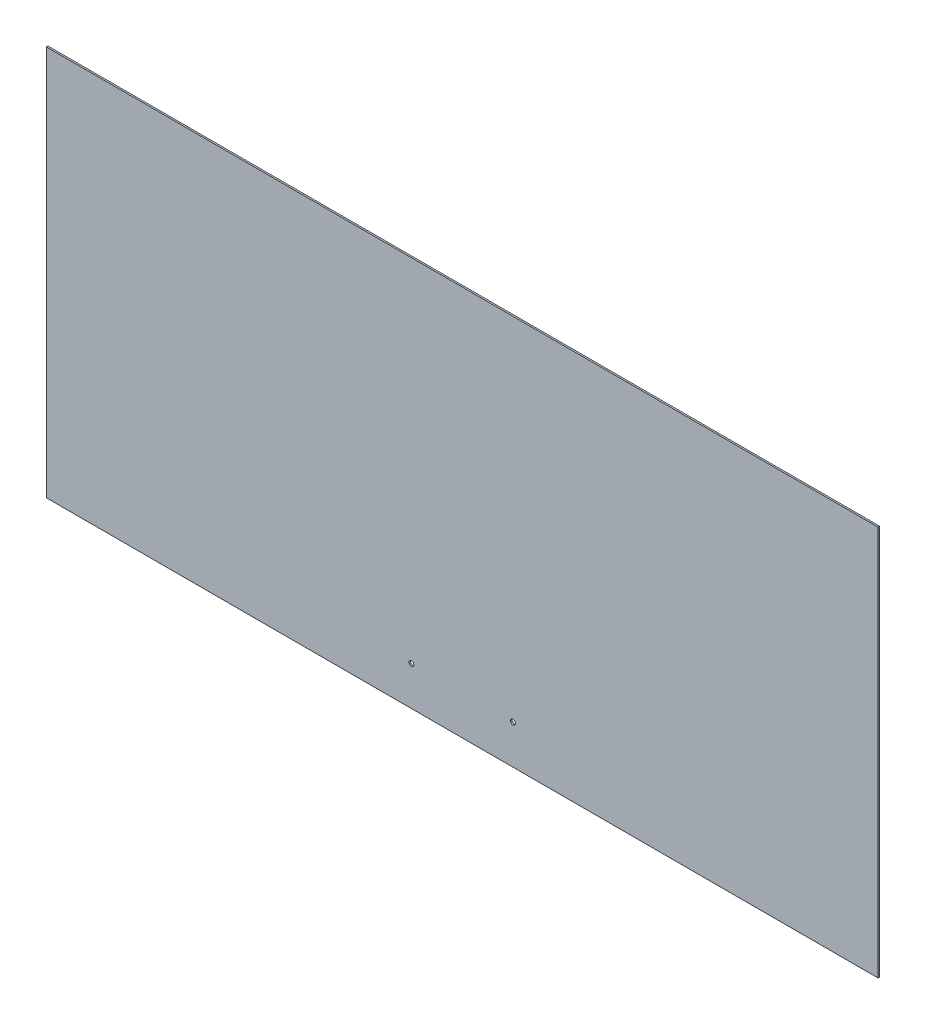
SolidWorks part; units mm, degrees
ref_plane "Front Plane" through (0, 0, 0) normal (0, 0, 1) x (1, 0, 0)
ref_plane "Top Plane" through (0, 0, 0) normal (0, 1, 0) x (1, 0, 0)
ref_plane "Right Plane" through (0, 0, 0) normal (1, 0, 0) x (0, 0, -1)
sketch "Sketch1" plane through (0, 0, 0) normal (0, 0, 1) x (1, 0, 0)
  line L1 (0, 0) -> (1065, 0)
  line L2 (0, 0) -> (0, -500)
  line L3 (0, -500) -> (1065, -500)
  line L4 (1065, 0) -> (1065, -500)
  dimension "D1" = 1065
  dimension "D2" = 500
extrude "Boss-Extrude1" add sketch "Sketch1" along normal blind 2
sketch "Sketch2" plane through (0, 0, 2) normal (0, 0, 1) x (1, 0, 0)
  line L0 (532.5, 0) -> (532.5, -500) construction
  line L1 (1065, 0) -> (0, 0) construction
  line L2 (0, -500) -> (1065, -500) construction
  line L3 (597.5, -450) -> (446.2041, -450) construction
  circle A0 centre (597.5, -450) radius 3.1
  circle A1 centre (467.5, -450) radius 3.1
  dimension "D1" = 6.2
  dimension "D2" = 130
  dimension "D3" = 50
extrude "Cut-Extrude1" cut sketch "Sketch2" against normal through all
